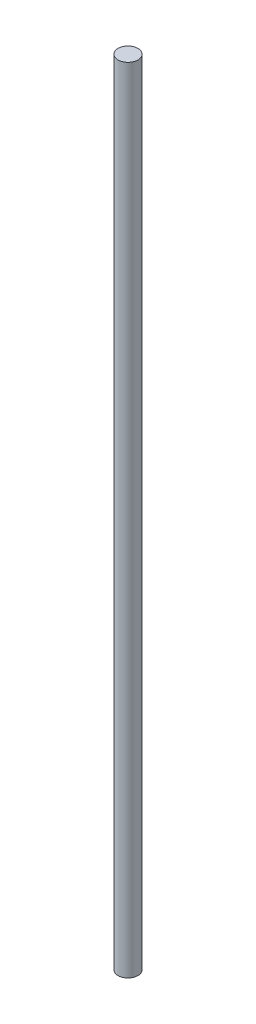
SolidWorks part; units mm, degrees
material "Carbon fibre"
ref_plane "Front Plane" through (0, 0, 0) normal (0, 0, 1) x (1, 0, 0)
ref_plane "Top Plane" through (0, 0, 0) normal (0, 1, 0) x (1, 0, 0)
ref_plane "Right Plane" through (0, 0, 0) normal (1, 0, 0) x (0, 0, -1)
sketch "Sketch1" plane through (0, 0, 0) normal (0, 1, 0) x (1, 0, 0)
  circle A0 centre (0, 0) radius 1.4
  dimension "D1" = 2.8
extrude "Boss-Extrude1" add sketch "Sketch1" along normal blind 111
